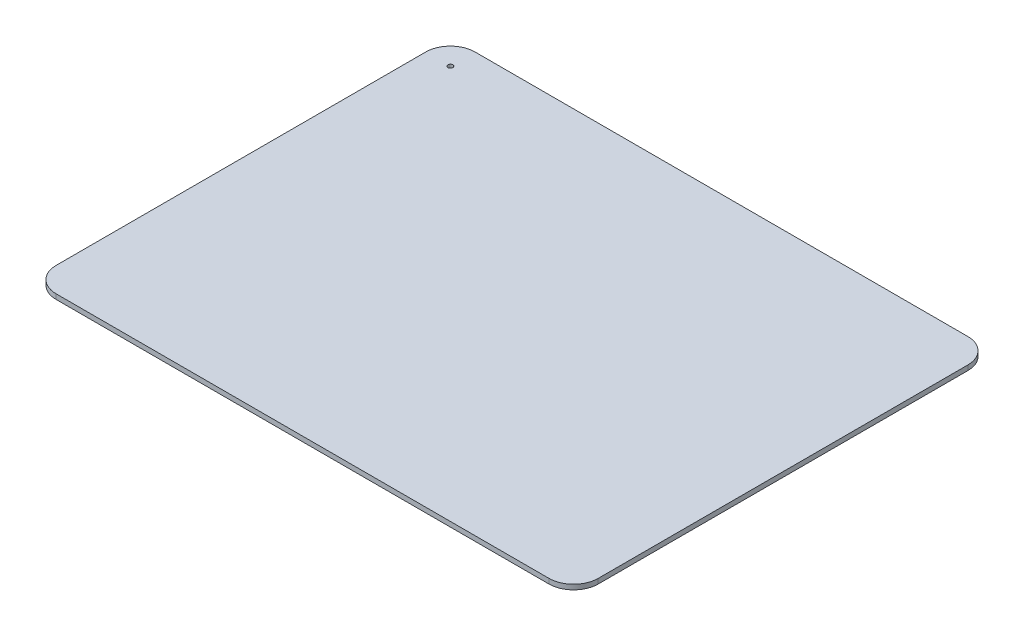
SolidWorks part; units mm, degrees
material "Teak"
ref_plane "Front Plane" through (0, 0, 0) normal (0, 0, 1) x (1, 0, 0)
ref_plane "Top Plane" through (0, 0, 0) normal (0, 1, 0) x (1, 0, 0)
ref_plane "Right Plane" through (0, 0, 0) normal (1, 0, 0) x (0, 0, -1)
sketch "Sketch1" plane through (0, 0, 0) normal (0, 1, 0) x (1, 0, 0)
  line L1 (-500, -425) -> (500, -425)
  line L2 (-550, -375) -> (-550, 375)
  line L3 (-500, 425) -> (500, 425)
  line L4 (550, -375) -> (550, 375)
  line L5 (-550, -425) -> (550, 425) construction
  line L6 (-550, 425) -> (550, -425) construction
  arc A0 (500, -425) -> (550, -375) centre (500, -375) ccw
  arc A1 (-550, 375) -> (-500, 425) centre (-500, 375) cw
  arc A2 (-500, -425) -> (-550, -375) centre (-500, -375) cw
  arc A3 (500, 425) -> (550, 375) centre (500, 375) cw
  point P0 (0, 0)
  dimension "D3" = 50
  dimension "D1" = 850
  dimension "D2" = 1100
extrude "Boss-Extrude1" add sketch "Sketch1" along normal blind 10
sketch "Sketch2" plane through (0, 10, 0) normal (0, 1, 0) x (1, 0, 0)
  circle A0 centre (-500, 375) radius 5
  arc A1 (-500, 425) -> (-550, 375) centre (-500, 375) ccw construction
  dimension "D1" = 10
extrude "Cut-Extrude1" cut sketch "Sketch2" against normal blind 50
